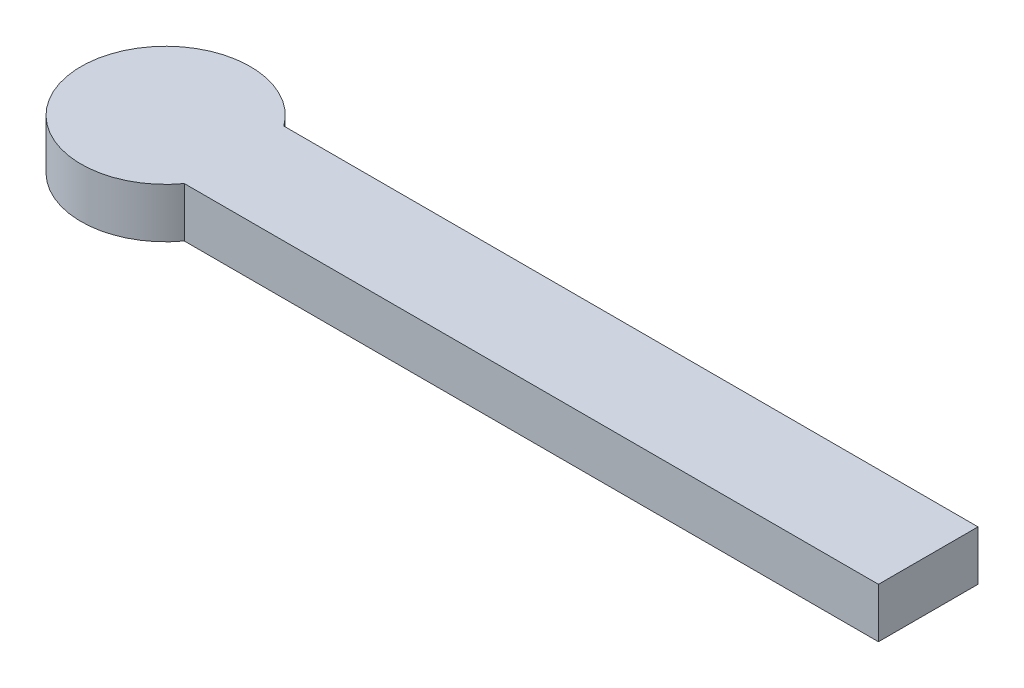
SolidWorks part; units mm, degrees
ref_plane "Plan de face" through (0, 0, 0) normal (0, 0, 1) x (1, 0, 0)
ref_plane "Plan de dessus" through (0, 0, 0) normal (0, 1, 0) x (1, 0, 0)
ref_plane "Plan de droite" through (0, 0, 0) normal (1, 0, 0) x (0, 0, -1)
sketch "Esquisse4" plane through (0, 0, 0) normal (0, 1, 0) x (1, 0, 0)
  line L1 (40, -5) -> (-40, -5)
  line L2 (40, -5) -> (40, 5)
  line L3 (40, 5) -> (-40, 5)
  line L4 (-40, -5) -> (-40, 5)
  line L5 (40, -5) -> (-40, 5) construction
  line L6 (40, 5) -> (-40, -5) construction
  point P0 (0, 0)
extrude "Boss.-Extru.3" add sketch "Esquisse4" along normal blind 5
sketch "Esquisse5" plane through (0, 5, 0) normal (0, 1, 0) x (1, 0, 0)
  circle A0 centre (-36.6073, 0) radius 8.5
extrude "Boss.-Extru.5" add sketch "Esquisse5" against normal blind 5 contours A0
